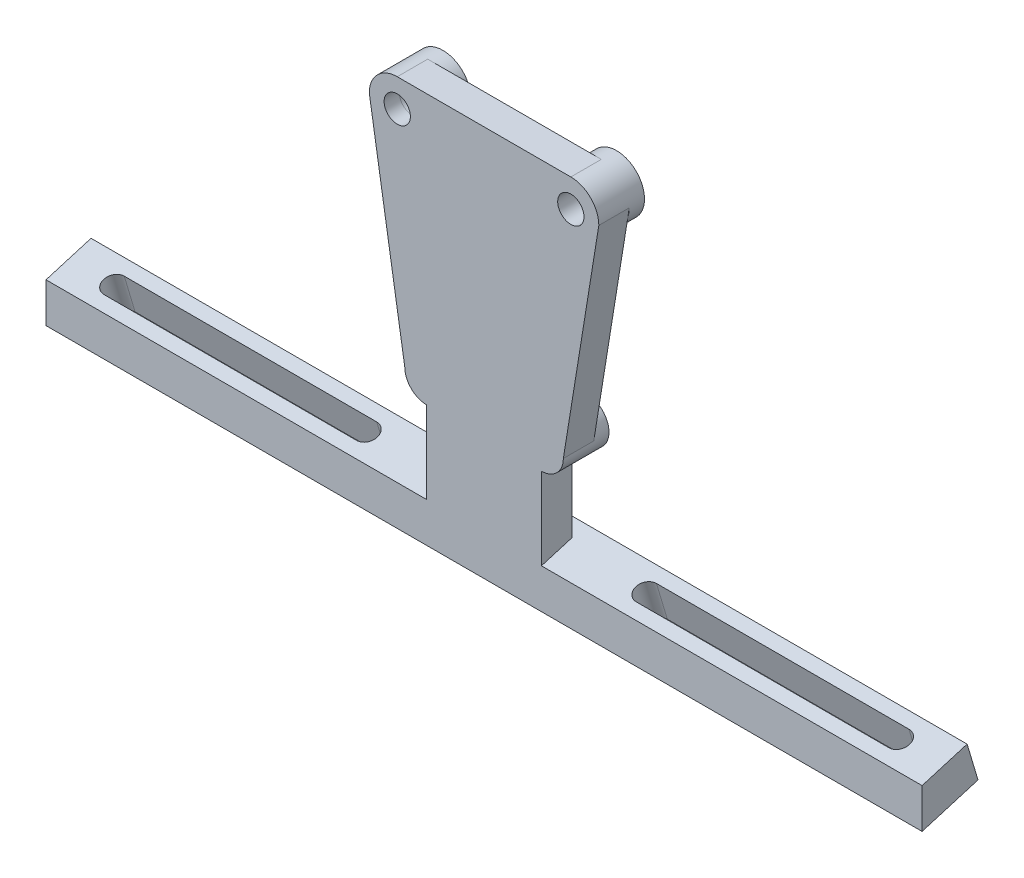
SolidWorks part; units mm, degrees
ref_plane "Front Plane" through (0, 0, 0) normal (0, 0, 1) x (1, 0, 0)
ref_plane "Top Plane" through (0, 0, 0) normal (0, 1, 0) x (1, 0, 0)
ref_plane "Right Plane" through (0, 0, 0) normal (1, 0, 0) x (0, 0, -1)
sketch "Sketch1" plane through (0, 0, 0) normal (0, 0, 1) x (1, 0, 0)
  line L0 (-36.9269, 41.15) -> (-36.9269, -2.1549)
  line L1 (-36.9269, -2.1549) -> (-28.3063, -2.1549)
  line L2 (1.3669, 41.15) -> (1.3669, -2.1549)
  line L3 (1.3669, -2.1549) -> (-36.9269, -2.1549)
  line L4 (-17.78, -2.1549) -> (-17.78, 48.8376)
  circle A0 centre (-3.3, 41.15) radius 2.1937
  circle A1 centre (-3.3, 41.15) radius 4.6669
  circle A2 centre (-32.26, 41.15) radius 2.1937
  circle A3 centre (-32.26, 41.15) radius 4.6669
  circle A4 centre (-8.202, 4.5091) radius 3.6492
  circle A5 centre (-27.358, 4.5091) radius 3.6492
extrude "Boss-Extrude1" add sketch "Sketch1" along normal blind 2.54 contours A4 | A1 A0 | A3 A2 | A5
sketch "Sketch2" plane through (0, 0, 2.54) normal (0, 0, 1) x (1, 0, 0)
  line L0 (-4.5528, 4.5091) -> (1.3669, 41.15)
  line L1 (-8.202, 0.8599) -> (-27.358, 0.8599)
  line L2 (-31.0072, 4.5091) -> (-36.9269, 41.15)
  line L3 (-3.3, 45.8169) -> (-32.26, 45.8169)
  circle A0 centre (-3.3, 41.15) radius 2.1937
  circle A1 centre (-32.26, 41.15) radius 2.2212
  circle A2 centre (-27.358, 4.5091) radius 3.6492 construction
  circle A3 centre (-8.202, 4.5091) radius 3.6492
  circle A4 centre (-8.202, 4.5091) radius 3.6492
  circle A5 centre (-32.26, 41.15) radius 4.6669 construction
  circle A6 centre (-3.3, 41.15) radius 4.6669 construction
  circle A7 centre (-27.358, 4.5091) radius 3.6492
  circle A8 centre (-32.26, 41.15) radius 4.6669
  circle A9 centre (-3.3, 41.15) radius 4.6669
  point P0 (-27.1913, 26.6627)
  circle M2 centre (-8.202, 4.5091) radius 3.6492
  dimension "D1" = 0
extrude "Boss-Extrude2" add sketch "Sketch2" along normal blind 2.54 contours A9 L3 A8 L2 A7 L1 L0 M2 | L0 A9 A0 | A8 L2 A1 | A7 | A4
sketch "Sketch4" plane through (0, 0, 5.08) normal (0, 0, 1) x (1, 0, 0)
  line L4 (-4.5528, 4.5091) -> (1.3669, 41.15)
  line L5 (-3.3, 45.8169) -> (-32.26, 45.8169)
  line L6 (-36.9269, 41.15) -> (-31.0072, 4.5091)
  line L7 (-27.358, 0.8599) -> (-8.202, 0.8599)
  line L8 (-4.5528, 4.5091) -> (1.3669, 41.15)
  line L9 (-3.3, 45.8169) -> (-32.26, 45.8169)
  line L10 (-36.9269, 41.15) -> (-31.0072, 4.5091)
  line L11 (-27.358, 0.8599) -> (-8.202, 0.8599)
  circle A0 centre (-3.3, 41.15) radius 2.1937 construction
  circle A1 centre (-32.26, 41.15) radius 2.1937 construction
  circle A2 centre (-3.3, 41.15) radius 2.1937
  circle A3 centre (-32.26, 41.15) radius 2.1937
  arc A4 (1.3669, 41.15) -> (-3.3, 45.8169) centre (-3.3, 41.15) ccw
  arc A5 (-32.26, 45.8169) -> (-36.9269, 41.15) centre (-32.26, 41.15) ccw
  arc A6 (-31.0072, 4.5091) -> (-27.358, 0.8599) centre (-27.358, 4.5091) ccw
  arc A7 (-8.202, 0.8599) -> (-4.5528, 4.5091) centre (-8.202, 4.5091) ccw
  arc A8 (1.3669, 41.15) -> (-3.3, 45.8169) centre (-3.3, 41.15) ccw
  arc A9 (-32.26, 45.8169) -> (-36.9269, 41.15) centre (-32.26, 41.15) ccw
  arc A10 (-31.0072, 4.5091) -> (-27.358, 0.8599) centre (-27.358, 4.5091) ccw
  arc A11 (-8.202, 0.8599) -> (-4.5528, 4.5091) centre (-8.202, 4.5091) ccw
  dimension "D1" = 0
extrude "Boss-Extrude3" add sketch "Sketch4" along normal blind 2.54
sketch "Sketch5" plane through (0, 0.8599, 0) normal (0, -1, 0) x (1, 0, 0)
  line L4 (-27.358, 2.54) -> (-8.202, 2.54)
  line L5 (-8.202, 2.54) -> (-8.202, 7.62)
  line L6 (-8.202, 7.62) -> (-27.358, 7.62)
  line L7 (-27.358, 7.62) -> (-27.358, 2.54)
  line L8 (-27.358, 2.54) -> (-8.202, 2.54)
  line L9 (-8.202, 2.54) -> (-8.202, 7.62)
  line L10 (-8.202, 7.62) -> (-27.358, 7.62)
  line L11 (-27.358, 7.62) -> (-27.358, 2.54)
  dimension "D1" = 0
extrude "Boss-Extrude4" add sketch "Sketch5" along normal up to surface (13.6804 mm away)
sketch "Sketch6" plane through (0, -9.6886, -2.8878) normal (0, -0.9583, -0.2856) x (1, 0, 0)
  line L4 (-27.358, 5.6637) -> (-8.202, 5.6637)
  line L5 (-8.202, 5.6637) -> (-8.202, 10.9646)
  line L6 (-8.202, 10.9646) -> (-27.358, 10.9646)
  line L7 (-27.358, 10.9646) -> (-27.358, 5.6637)
  line L8 (-27.358, 5.6637) -> (-8.202, 5.6637)
  line L9 (-8.202, 5.6637) -> (-8.202, 10.9646)
  line L10 (-8.202, 10.9646) -> (-27.358, 10.9646)
  line L11 (-27.358, 10.9646) -> (-27.358, 5.6637)
  dimension "D1" = 0
extrude "Boss-Extrude5" add sketch "Sketch6" along normal blind 6.35
sketch "Sketch7" plane through (0, -15.774, -4.7016) normal (0, -0.9583, -0.2856) x (1, 0, 0)
  line L1 (-8.202, 5.6637) -> (55.298, 5.6637)
  line L2 (-8.202, 5.6637) -> (-8.202, 14.5537)
  line L3 (-8.202, 14.5537) -> (55.298, 14.5537)
  line L4 (-27.358, 10.9646) -> (-27.358, 5.6637)
  line L5 (-27.358, 5.6637) -> (-8.202, 5.6637)
  line L6 (-8.202, 5.6637) -> (-8.202, 10.9646)
  line L7 (-8.202, 10.9646) -> (-27.358, 10.9646)
  line L8 (-27.358, 10.9646) -> (-27.358, 5.6637)
  line L9 (-27.358, 5.6637) -> (-8.202, 5.6637)
  line L10 (-8.202, 5.6637) -> (-8.202, 10.9646)
  line L11 (-8.202, 10.9646) -> (-27.358, 10.9646)
  line L12 (55.298, 5.6637) -> (55.298, 14.5537)
  line L13 (-27.358, 5.6637) -> (-90.858, 5.6637)
  line L14 (-27.358, 5.6637) -> (-27.358, 14.5537)
  line L15 (-27.358, 14.5537) -> (-90.858, 14.5537)
  line L16 (-90.858, 5.6637) -> (-90.858, 14.5537)
  line L17 (-8.202, 14.5537) -> (-27.358, 14.5537)
  line L18 (-8.202, 14.5537) -> (-8.202, 10.9646)
  line L19 (-8.202, 10.9646) -> (-27.358, 10.9646)
  line L20 (-27.358, 14.5537) -> (-27.358, 10.9646)
  line M11 (-27.358, 10.9646) -> (-27.358, 5.6637)
  line M12 (-27.358, 5.6637) -> (-8.202, 5.6637)
  line M13 (-8.202, 5.6637) -> (-8.202, 10.9646)
  line M14 (-8.202, 10.9646) -> (-27.358, 10.9646)
  dimension "D3" = 8.89
  dimension "D4" = 63.5
  dimension "D5" = 63.5
  dimension "D1" = 0
extrude "Boss-Extrude6" add sketch "Sketch7" against normal up to surface (6.35 mm away) contours L16 L13 L14 L15 M11 | L2 L17 L14 M14 | M14 M11 M12 M13 | L1 L12 L3 L2 M13
sketch "Sketch9" plane through (0, 45.8169, 0) normal (0, 1, 0) x (1, 0, 0)
  line L0 (-27.358, -7.62) -> (-8.202, -7.62) construction
  line L1 (-17.78, -7.62) -> (77.0219, -7.62)
  line L2 (-17.78, -7.62) -> (-17.78, -45.9559)
  line L3 (-17.78, -45.9559) -> (77.0219, -45.9559)
  line L4 (77.0219, -7.62) -> (77.0219, -45.9559)
  line L6 (-17.78, -7.62) -> (-120.5206, -7.62)
  line L7 (-17.78, -7.62) -> (-17.78, -45.9559)
  line L8 (-17.78, -45.9559) -> (-120.5206, -45.9559)
  line L9 (-120.5206, -7.62) -> (-120.5206, -45.9559)
  line M3 (-32.26, -7.62) -> (-3.3, -7.62)
extrude "Cut-Extrude1" cut sketch "Sketch9" against normal through all contours L4 L1 L2 L3 M3 | L6 L9 L8 L2 M3
sketch "Sketch10" plane through (0, -1.6178, 5.4278) normal (0, 0.2856, -0.9583) x (-1, 0, 0)
  line L6 (27.358, -10.1098) -> (8.202, -10.1098)
  line L7 (8.202, -10.1098) -> (-55.298, -10.1098)
  line L8 (-55.298, -10.1098) -> (-55.298, -16.4598)
  line L9 (-55.298, -16.4598) -> (90.858, -16.4598)
  line L10 (90.858, -16.4598) -> (90.858, -10.1098)
  line L11 (90.858, -10.1098) -> (27.358, -10.1098)
  line L12 (27.358, -10.1098) -> (8.202, -10.1098)
  line L13 (8.202, -10.1098) -> (-55.298, -10.1098)
  line L14 (-55.298, -10.1098) -> (-55.298, -16.4598)
  line L15 (-55.298, -16.4598) -> (90.858, -16.4598)
  line L16 (90.858, -16.4598) -> (90.858, -10.1098)
  line L17 (90.858, -10.1098) -> (27.358, -10.1098)
  dimension "D1" = 0
extrude "Boss-Extrude7" add sketch "Sketch10" along normal blind 2.54
sketch "Sketch11" plane through (0, -9.6886, -2.8878) normal (0, 0.9583, 0.2856) x (1, 0, 0)
  line L0 (-83.238, -5.2942) -> (-41.1096, -5.2942)
  line L1 (-90.858, -3.1237) -> (-90.858, -10.9646) construction
  line L2 (-90.858, -10.9646) -> (55.298, -10.9646)
  line L3 (-83.238, -7.0442) -> (-90.858, -7.0442)
  line L4 (-41.1096, -5.2942) -> (-41.1096, -8.7942)
  line L5 (-41.1096, -8.7942) -> (-83.238, -8.7942)
  line L6 (-17.78, -10.9646) -> (-17.78, 17.375)
  line L7 (5.5496, -8.7942) -> (47.678, -8.7942)
  line L8 (47.678, -5.2942) -> (5.5496, -5.2942)
  circle A1 centre (-83.238, -7.0442) radius 1.75
  circle A2 centre (-41.1096, -7.0442) radius 1.75
  circle A3 centre (47.678, -7.0442) radius 1.75
  circle A4 centre (5.5496, -7.0442) radius 1.75
  dimension "D1" = 3.5
extrude "Cut-Extrude2" cut sketch "Sketch11" against normal through all and the other way through all
